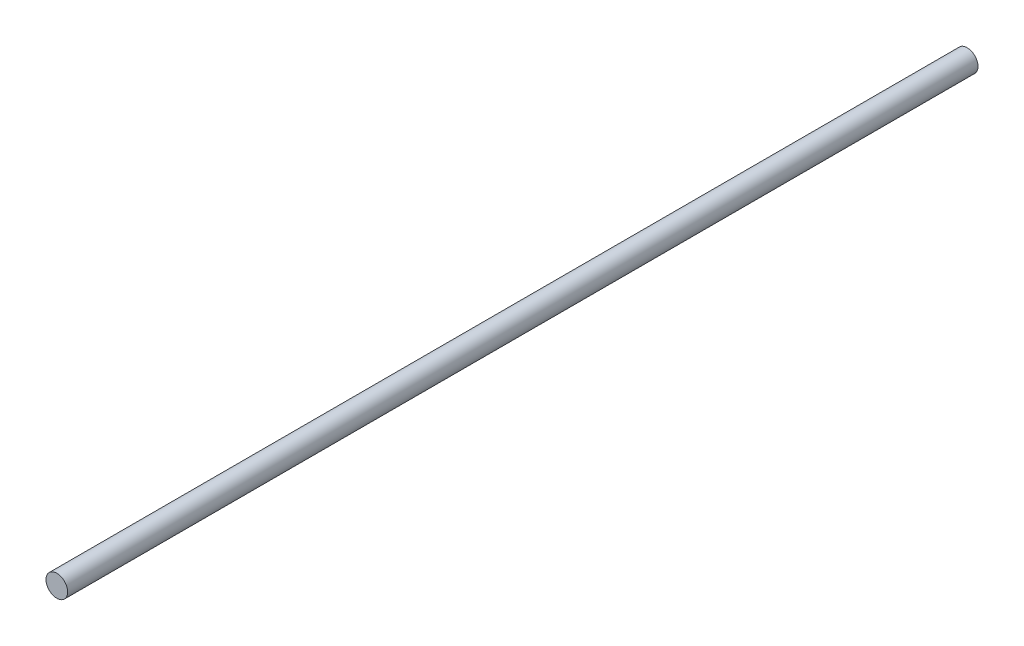
SolidWorks part; units mm, degrees
ref_plane "前视基准面" through (0, 0, 0) normal (0, 0, 1) x (1, 0, 0)
ref_plane "上视基准面" through (0, 0, 0) normal (0, 1, 0) x (1, 0, 0)
ref_plane "右视基准面" through (0, 0, 0) normal (1, 0, 0) x (0, 0, -1)
sketch "草图1" plane through (0, 0, 0) normal (0, 0, 1) x (1, 0, 0)
  circle A0 centre (0, 0) radius 4
  dimension "D1" = 8
extrude "凸台-拉伸1" add sketch "草图1" along normal blind 335.9
